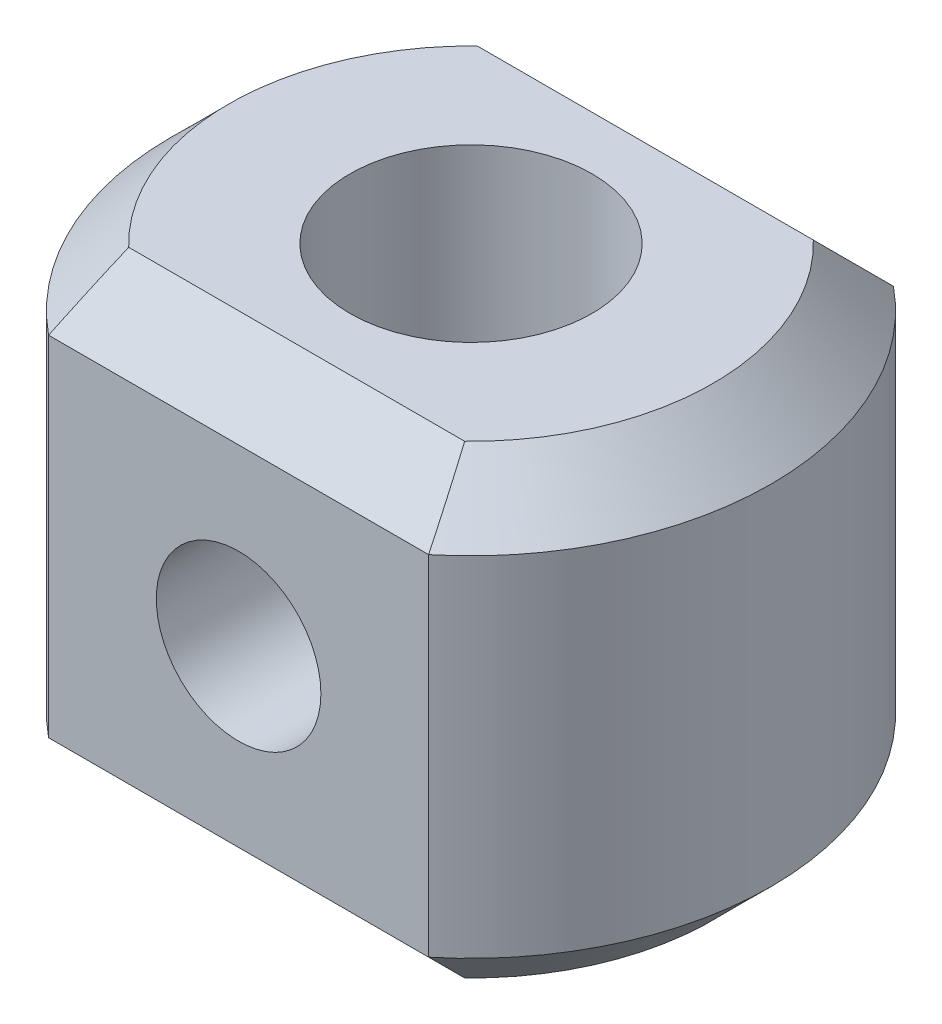
SolidWorks part; units mm, degrees
material "Gray Cast Iron"
ref_plane "Front Plane" through (0, 0, 0) normal (0, 0, 1) x (1, 0, 0)
ref_plane "Top Plane" through (0, 0, 0) normal (0, 1, 0) x (1, 0, 0)
ref_plane "Right Plane" through (0, 0, 0) normal (1, 0, 0) x (0, 0, -1)
sketch "Sketch2" plane through (0, 0, 0) normal (0, 1, 0) x (1, 0, 0)
  line L0 (-19.6214, 24) -> (19.6214, 24)
  line L1 (-19.6214, -24) -> (19.6214, -24)
  circle A0 centre (0, 0) radius 12.5
  arc A1 (-19.6214, 24) -> (-19.6214, -24) centre (0, 0) ccw
  arc A2 (19.6214, -24) -> (19.6214, 24) centre (0, 0) ccw
  dimension "D2" = 25
  dimension "D3" = 62
  dimension "D1" = 48
extrude "Boss-Extrude1" add sketch "Sketch2" along normal mid plane 48
sketch "Sketch1" plane through (0, 0, 0) normal (0, 0, 1) x (1, 0, 0)
  circle A0 centre (0, 0) radius 8.5
  dimension "D1" = 17
extrude "Cut-Extrude1" cut sketch "Sketch1" against normal through all both and the other way through all
chamfer "Chamfer1" distance 6 angle 45 8 edges at (-31, -24, 0) (0, -24, -24) (31, -24, 0) (0, -24, 24) (0, 24, -24) (31, 24, 0) (0, 24, 24) (-31, 24, 0)
